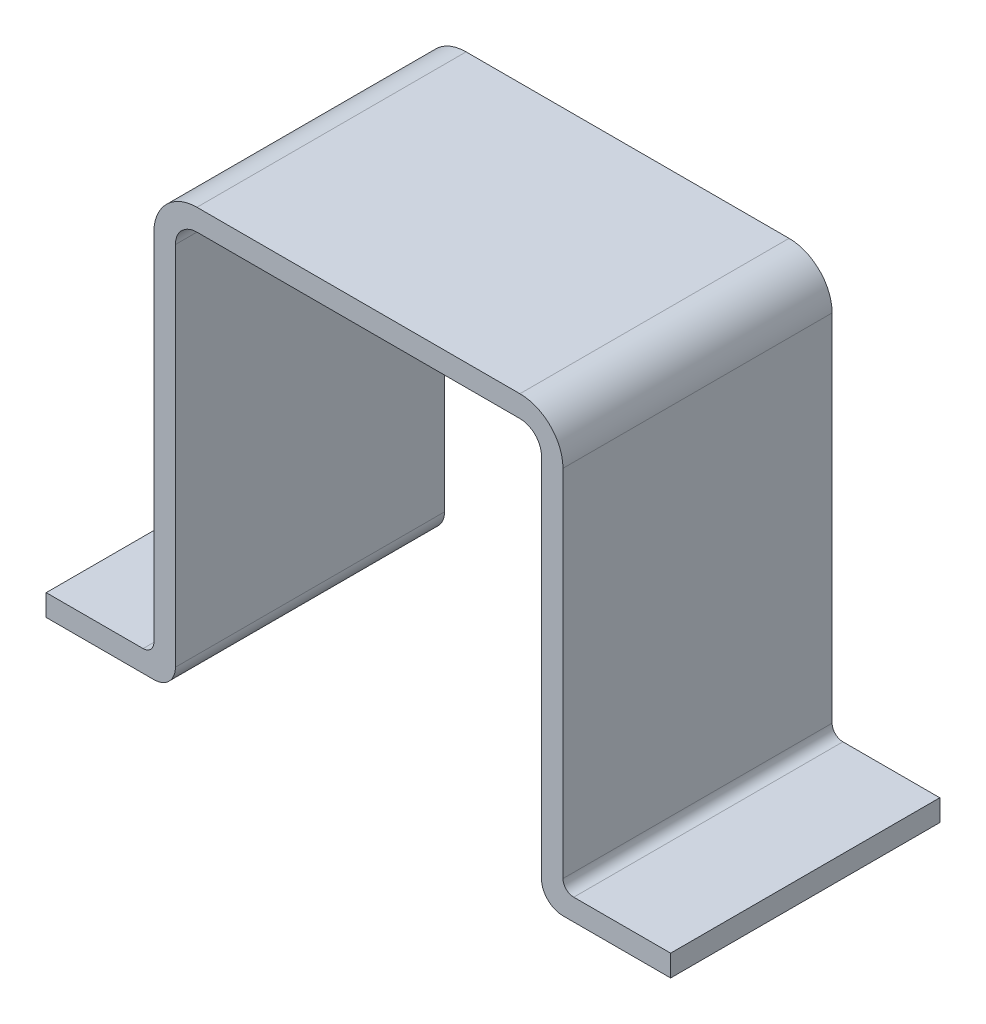
SolidWorks part; units mm, degrees
ref_plane "Plan de face" through (0, 0, 0) normal (0, 0, 1) x (1, 0, 0)
ref_plane "Plan de dessus" through (0, 0, 0) normal (0, 1, 0) x (1, 0, 0)
ref_plane "Plan de droite" through (0, 0, 0) normal (1, 0, 0) x (0, 0, -1)
sketch "Esquisse1" plane through (0, 0, 0) normal (0, 0, 1) x (1, 0, 0)
  line L0 (-32.3733, 0) -> (-22.3733, 0)
  line L1 (-20.3733, 2) -> (-20.3733, 36)
  line L2 (-18.3733, 38) -> (11.6267, 38)
  line L3 (13.6267, 36) -> (13.6267, 2)
  line L4 (15.6267, 0) -> (25.6267, 0)
  arc A0 (-20.3733, 36) -> (-18.3733, 38) centre (-18.3733, 36) cw
  arc A1 (11.6267, 38) -> (13.6267, 36) centre (11.6267, 36) cw
  arc A2 (15.6267, 0) -> (13.6267, 2) centre (15.6267, 2) cw
  arc A3 (-22.3733, 0) -> (-20.3733, 2) centre (-22.3733, 2) ccw
  dimension "D2" = 2
  dimension "D5" = 2
  dimension "D6" = 2
  dimension "D7" = 2
  dimension "D1" = 10
  dimension "D3" = 38
  dimension "D4" = 34
  dimension "D8" = 10
extrude "Extru.-Mince1" add sketch "Esquisse1" along normal blind 25 thin
fillet "Congé1" radius 1 2 edges at (15.6267, 2, 12.5) (-22.3733, 2, 12.5)
